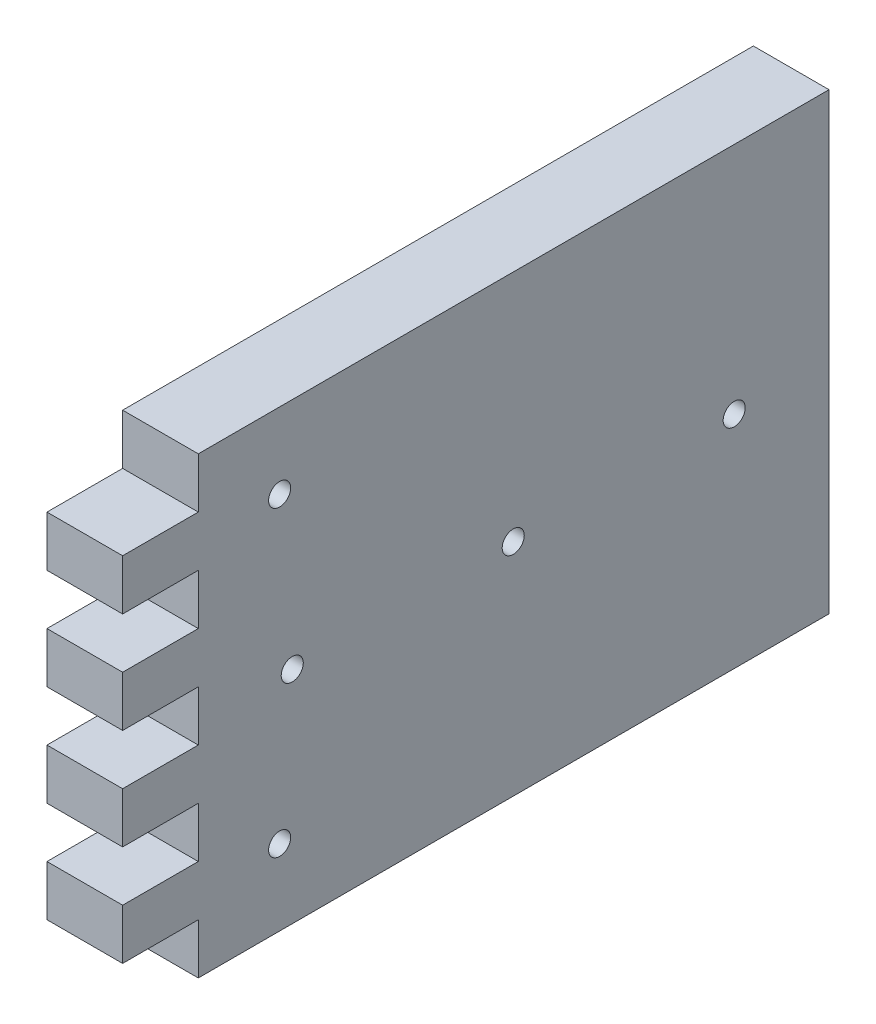
SolidWorks part; units mm, degrees
material "6061-T6 (SS)"
ref_plane "Front Plane" through (0, 0, 0) normal (0, 0, 1) x (1, 0, 0)
ref_plane "Top Plane" through (0, 0, 0) normal (0, 1, 0) x (1, 0, 0)
ref_plane "Right Plane" through (0, 0, 0) normal (1, 0, 0) x (0, 0, -1)
sketch "Sketch1" plane through (0, 0, 0) normal (1, 0, 0) x (0, 0, -1)
  line L0 (19.05, 101.6) -> (19.05, 88.9) construction
  line L1 (19.05, 0) -> (177.8635, 0)
  line L2 (0, 12.7) -> (0, 25.4)
  line L3 (19.05, 114.3) -> (177.8635, 114.3)
  line L5 (177.8635, 114.3) -> (177.8635, 0)
  line L13 (0, 101.6) -> (19.05, 101.6)
  line L14 (19.05, 114.3) -> (19.05, 101.6)
  line L17 (0, 88.9) -> (19.05, 88.9)
  line L19 (0, 76.2) -> (19.05, 76.2)
  line L20 (19.05, 88.9) -> (19.05, 76.2)
  line L21 (0, 88.9) -> (19.05, 76.2) construction
  line L22 (0, 76.2) -> (19.05, 88.9) construction
  line L23 (0, 63.5) -> (19.05, 63.5)
  line L25 (0, 50.8) -> (19.05, 50.8)
  line L26 (19.05, 63.5) -> (19.05, 50.8)
  line L27 (0, 63.5) -> (19.05, 50.8) construction
  line L28 (0, 50.8) -> (19.05, 63.5) construction
  line L29 (0, 38.1) -> (19.05, 38.1)
  line L31 (0, 25.4) -> (19.05, 25.4)
  line L32 (19.05, 38.1) -> (19.05, 25.4)
  line L33 (0, 38.1) -> (19.05, 25.4) construction
  line L34 (0, 25.4) -> (19.05, 38.1) construction
  line L37 (0, 12.7) -> (19.05, 12.7)
  line L38 (19.05, 0) -> (19.05, 12.7)
  line L41 (19.05, 76.2) -> (19.05, 63.5) construction
  line L42 (19.05, 50.8) -> (19.05, 38.1) construction
  line L43 (19.05, 25.4) -> (19.05, 12.7) construction
  line L44 (0, 88.9) -> (0, 101.6)
  line L45 (0, 63.5) -> (0, 76.2)
  line L46 (0, 38.1) -> (0, 50.8)
  point P4 (177.8635, 55.88)
  point P14 (9.525, 82.55)
  point P19 (9.525, 57.15)
  point P24 (9.525, 31.75)
  dimension "D1" = 114.3
  dimension "D2" = 158.8135
  dimension "D3" = 12.7
  dimension "D4" = 19.05
extrude "Boss-Extrude1" add sketch "Sketch1" along normal blind 19.05
hole_wizard "7/32 (0.21875) Diameter Hole3" positions "Sketch3" profile "Sketch4" hole size "7/32" standard "ANSI Inch" end condition up to next
sketch "Sketch3" plane through (19.05, 0, 0) normal (1, 0, 0) x (0, 0, -1)
  line L1 (177.8635, 55.499) -> (153.9875, 55.499) construction
  line L2 (177.8635, 0) -> (177.8635, 114.3) construction
  line L3 (153.9875, 55.499) -> (98.3488, 55.499) construction
  line L4 (98.3488, 55.499) -> (42.7101, 55.499) construction
  line L5 (19.05, 0) -> (177.8635, 0) construction
  line L7 (177.8635, 114.3) -> (19.05, 114.3) construction
  line L13 (39.5351, 114.3) -> (39.5351, 95.25) construction
  line L14 (39.5351, 95.25) -> (39.5351, 19.05) construction
  line L15 (39.5351, 19.05) -> (39.5351, 0) construction
  point P10 (153.9875, 55.499)
  point P14 (98.3488, 55.499)
  point P16 (42.7101, 55.499)
  point P47 (39.5351, 95.25)
  point P49 (39.5351, 19.05)
  dimension "D1" = 23.876
  dimension "D2" = 55.6387
  dimension "D3" = 55.499
  dimension "D4" = 6.35
  dimension "D6" = 19.05
sketch "Sketch4" plane through (19.05, 19.05, -39.5351) normal (0, 1, 0) x (0, 0, -1)
  line L0 (0, 0) -> (0, 19.05)
  line L1 (0, 19.05) -> (2.7781, 19.05)
  line L2 (2.7781, 19.05) -> (2.7781, 0)
  line L5 (2.7781, 0) -> (0, 0)
  line L11 (0, -6.35) -> (0, 107.95) construction
  dimension "Thru Hole Dia." = 5.5562
  dimension "Thru Hole Depth" = 19.05
